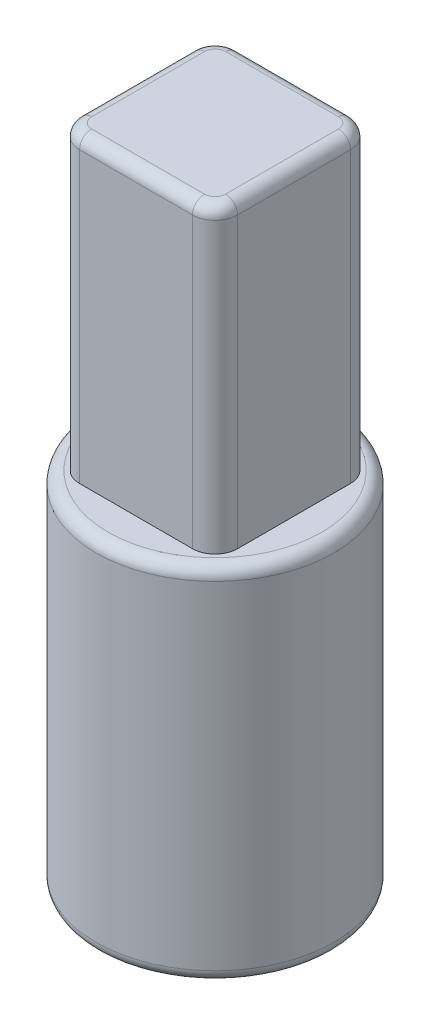
SolidWorks part; units mm, degrees
ref_plane "Front" through (0, 0, 0) normal (0, 0, 1) x (1, 0, 0)
ref_plane "Top" through (0, 0, 0) normal (0, 1, 0) x (1, 0, 0)
ref_plane "Right" through (0, 0, 0) normal (1, 0, 0) x (0, 0, -1)
sketch "Sketch1" plane through (0, 0, 0) normal (0, 1, 0) x (1, 0, 0)
  circle A0 centre (0, 0) radius 3.95
  dimension "D1" = 7.9
extrude "Boss-Extrude1" add sketch "Sketch1" along normal blind 12
sketch "Sketch2" plane through (0, 12, 0) normal (0, 1, 0) x (1, 0, 0)
  line L1 (-2.625, 2.625) -> (2.625, 2.625)
  line L2 (-2.625, 2.625) -> (-2.625, -2.625)
  line L3 (-2.625, -2.625) -> (2.625, -2.625)
  line L4 (2.625, 2.625) -> (2.625, -2.625)
  point P4 (0, -2.625)
  point P5 (-2.625, 0)
  dimension "D1" = 5.25
extrude "Boss-Extrude2" add sketch "Sketch2" along normal blind 10
sketch "Sketch3" plane through (0, 0, 0) normal (0, -1, 0) x (1, 0, 0)
  line L0 (1.025, -1.5401) -> (-1.025, -1.5401)
  arc A0 (1.025, -1.5401) -> (-1.025, -1.5401) centre (0, 0) ccw
  dimension "D1" = 1.85
  dimension "D2" = 2.05
extrude "Cut-Extrude1" cut sketch "Sketch3" against normal blind 11
fillet "Fillet1" radius 0.75 4 edges at (2.625, 17, 2.625) (2.625, 17, -2.625) (-2.625, 17, -2.625) (-2.625, 17, 2.625)
fillet "Fillet2" radius 0.4 12 edges at (0, 0, 3.95) (0, 0, -1.5401) (0, 0, 1.85) (0, 12, 3.95) (-2.4053, 22, -2.4053) (0, 22, -2.625) (2.4053, 22, -2.4053) (2.625, 22, 0) (2.4053, 22, 2.4053) (0, 22, 2.625) (-2.4053, 22, 2.4053) (-2.625, 22, 0)
